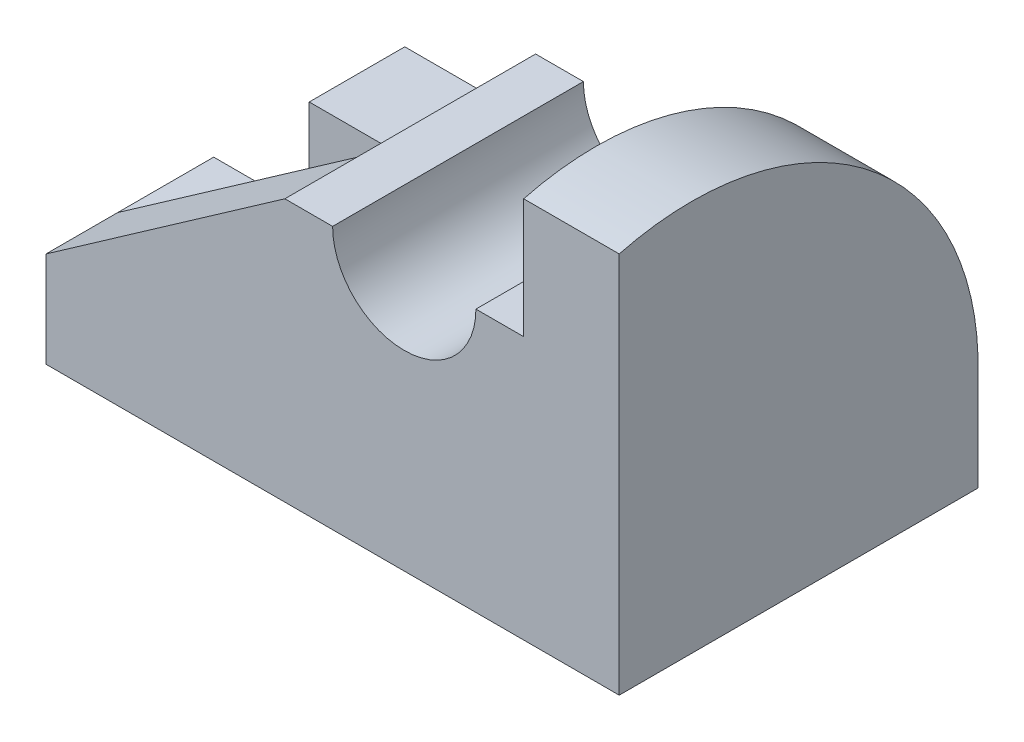
SolidWorks part; units mm, degrees
ref_plane "Front Plane" through (0, 0, 0) normal (0, 0, 1) x (1, 0, 0)
ref_plane "Top Plane" through (0, 0, 0) normal (0, 1, 0) x (1, 0, 0)
ref_plane "Right Plane" through (0, 0, 0) normal (1, 0, 0) x (0, 0, -1)
sketch "Sketch1" plane through (0, 0, 0) normal (0, 1, 0) x (1, 0, 0)
  line L1 (-48, -30.0426) -> (48, -30.0426)
  line L2 (-48, -30.0426) -> (-48, 30.0426)
  line L3 (-48, 30.0426) -> (48, 30.0426)
  line L4 (48, -30.0426) -> (48, 30.0426)
  line L5 (-48, -30.0426) -> (48, 30.0426) construction
  line L6 (-48, 30.0426) -> (48, -30.0426) construction
  point P0 (0, 0)
  dimension "D1" = 96
  dimension "D2" = 60.0851
extrude "Boss-Extrude2" add sketch "Sketch1" along normal blind 16
sketch "Sketch4" plane through (48, 0, 0) normal (1, 0, 0) x (0, 0, -1)
  line L0 (-30.0426, 16) -> (-30.0426, 64)
  line L1 (-30.0426, 0) -> (30.0426, 0) construction
  line L6 (-30.0426, 0) -> (30.0426, 0)
  line L7 (30.0426, 0) -> (30.0426, 16)
  line L8 (30.0426, 16) -> (-30.0426, 16)
  line L9 (-30.0426, 16) -> (-30.0426, 0)
  line L10 (-30.0426, 0) -> (30.0426, 0)
  line L11 (30.0426, 0) -> (30.0426, 16)
  line L13 (-30.0426, 16) -> (-30.0426, 0)
  arc A0 (-30.0426, 64) -> (30.0426, 16) centre (-17.9323, 17.5528) cw
  dimension "D2" = 48
  dimension "D1" = 64
  dimension "D3" = 0
extrude "Boss-Extrude3" add sketch "Sketch4" against normal blind 16
sketch "Sketch5" plane through (0, 16, 0) normal (0, 1, 0) x (1, 0, 0)
  line L1 (32, -30.0426) -> (-8, -30.0426)
  line L2 (32, -30.0426) -> (32, 11.9574)
  line L3 (32, 11.9574) -> (-8, 11.9574)
  line L4 (-8, -30.0426) -> (-8, 11.9574)
  dimension "D1" = 40
  dimension "D2" = 42
extrude "Boss-Extrude4" add sketch "Sketch5" along normal blind 28
sketch "Sketch6" plane through (0, 0, 30.0426) normal (0, 0, 1) x (1, 0, 0)
  line L0 (-8, 44) -> (32, 44) construction
  circle A0 centre (12, 44) radius 12
  dimension "D1" = 24
extrude "Cut-Extrude1" cut sketch "Sketch6" against normal blind 43
sketch "Sketch10" plane through (0, 0, 30.0426) normal (0, 0, 1) x (1, 0, 0)
  line L0 (-8, 44) -> (-48, 16)
  line L1 (-48, 16) -> (-8, 16)
  line L2 (-8, 16) -> (-8, 44)
extrude "Boss-Extrude6" add sketch "Sketch10" against normal blind 12
sketch "Sketch11" plane through (0, 16, 0) normal (0, 1, 0) x (1, 0, 0)
  line L0 (-48, 30.0426) -> (-48, -18.0426) construction
  line L1 (-48, 14.0426) -> (-28, 14.0426)
  line L2 (-48, 14.0426) -> (-48, -1.9574)
  line L3 (-48, -1.9574) -> (-28, -1.9574)
  line L4 (-28, 14.0426) -> (-28, -1.9574)
  circle A0 centre (-28, 6.0426) radius 8
  line M7 (-48, 30.0426) -> (-48, -18.0426)
  dimension "D4" = 16
  dimension "D2" = 16
  dimension "D3" = 20
extrude "Cut-Extrude2" cut sketch "Sketch11" against normal blind 16 contours A0 L1 L3 M7 | L4 A0 | L4 A0
